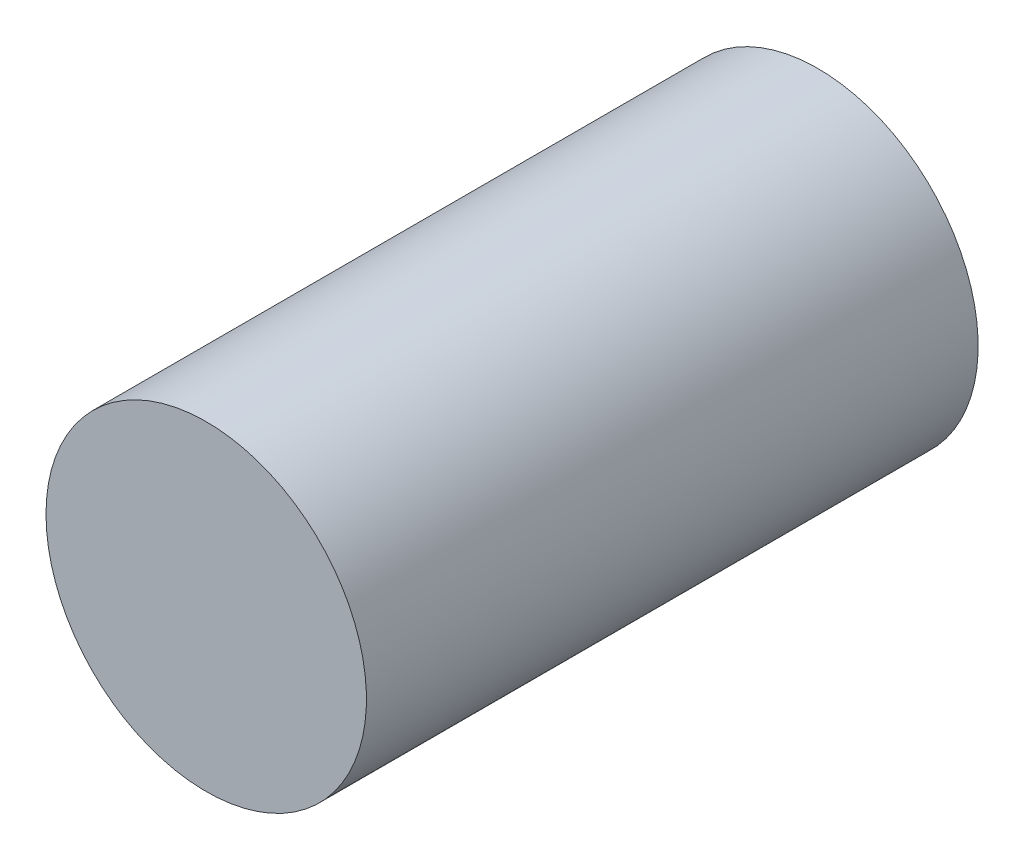
SolidWorks part; units mm, degrees
ref_plane "Front Plane" through (0, 0, 0) normal (0, 0, 1) x (1, 0, 0)
ref_plane "Top Plane" through (0, 0, 0) normal (0, 1, 0) x (1, 0, 0)
ref_plane "Right Plane" through (0, 0, 0) normal (1, 0, 0) x (0, 0, -1)
sketch "Sketch1" plane through (0, 0, 0) normal (0, 0, 1) x (1, 0, 0)
  circle A0 centre (0, 0) radius 5.5
extrude "Envelope" add sketch "Sketch1" along normal blind 21
